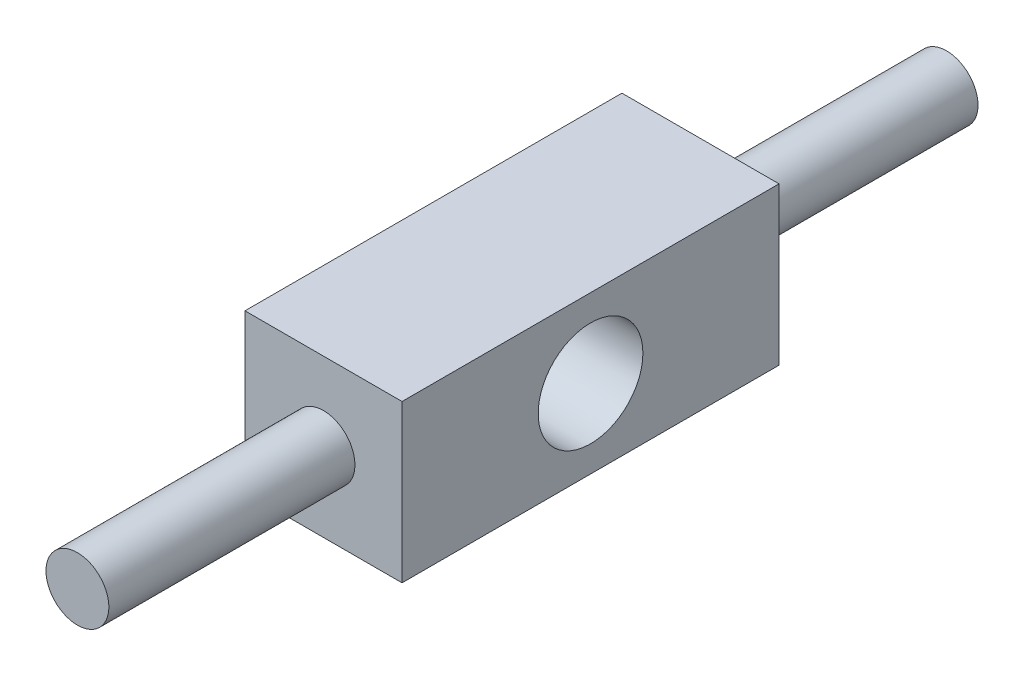
SolidWorks part; units mm, degrees
ref_plane "Front Plane" through (0, 0, 0) normal (0, 0, 1) x (1, 0, 0)
ref_plane "Top Plane" through (0, 0, 0) normal (0, 1, 0) x (1, 0, 0)
ref_plane "Right Plane" through (0, 0, 0) normal (1, 0, 0) x (0, 0, -1)
sketch "Sketch1" plane through (0, 0, 0) normal (0, 0, 1) x (1, 0, 0)
  line L1 (-52.6086, 27.2858) -> (47.3914, 27.2858)
  line L2 (-52.6086, 27.2858) -> (-52.6086, -72.7142)
  line L3 (-52.6086, -72.7142) -> (47.3914, -72.7142)
  line L4 (47.3914, 27.2858) -> (47.3914, -72.7142)
sketch "Sketch2" plane through (0, 0, 0) normal (0, 0, 1) x (1, 0, 0)
  line L0 (-52.6086, 77.2858) -> (97.3914, 77.2858)
  line L1 (-52.6086, 77.2858) -> (-52.6086, -72.7142)
  line L2 (-52.6086, -72.7142) -> (97.3914, -72.7142)
  line L3 (97.3914, 77.2858) -> (97.3914, -72.7142)
extrude "Boss-Extrude1" add sketch "Sketch2" along normal blind 180
sketch "Sketch3" plane through (0, 0, 180) normal (0, 0, 1) x (1, 0, 0)
  line L0 (97.3914, 77.2858) -> (-52.6086, -72.7142) construction
  circle A0 centre (22.3914, 2.2858) radius 30
sketch "Sketch4" plane through (0, 0, 180) normal (0, 0, 1) x (1, 0, 0)
sketch "Sketch5" plane through (0, 0, 180) normal (0, 0, 1) x (1, 0, 0)
  circle A0 centre (22.3914, 2.2858) radius 30
extrude "Boss-Extrude3" add sketch "Sketch5" along normal blind 235
mirror "Mirror1" about plane through (0, 0, 0) normal (0, 0, 1) of "Boss-Extrude3", "Boss-Extrude1"
sketch "Sketch6" plane through (97.3914, 0, 0) normal (1, 0, 0) x (0, 0, -1)
  line L0 (0, 77.2858) -> (0, -72.7142) construction
  line L1 (-180, 77.2858) -> (180, 77.2858) construction
  line L2 (-180, -72.7142) -> (180, -72.7142) construction
  circle A0 centre (0, 2.2858) radius 50
sketch "Sketch7" plane through (97.3914, 0, 0) normal (1, 0, 0) x (0, 0, -1)
  circle A0 centre (0, 2.2858) radius 50
extrude "Cut-Extrude1" cut sketch "Sketch7" against normal through all
